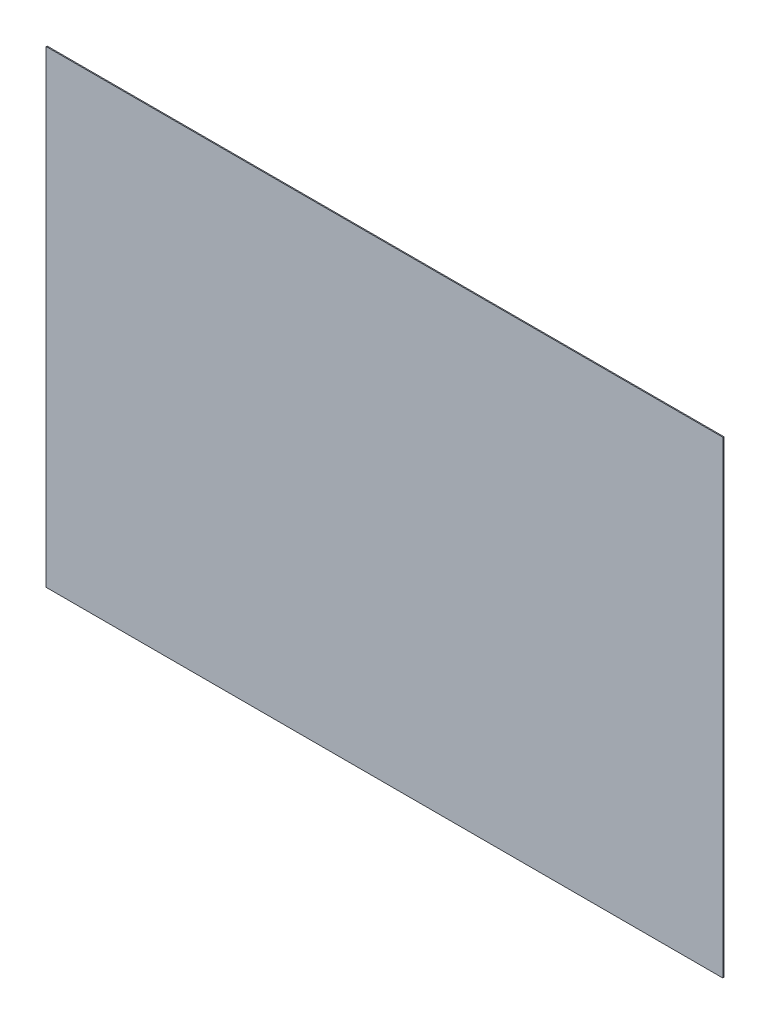
SolidWorks part; units mm, degrees
ref_plane "Alzado" through (0, 0, 0) normal (0, 0, 1) x (1, 0, 0)
ref_plane "Planta" through (0, 0, 0) normal (0, 1, 0) x (1, 0, 0)
ref_plane "Vista lateral" through (0, 0, 0) normal (1, 0, 0) x (0, 0, -1)
sketch "Croquis1" plane through (0, 0, 0) normal (0, 0, 1) x (1, 0, 0)
  line L1 (-650, 450) -> (650, 450)
  line L2 (-650, 450) -> (-650, -450)
  line L3 (-650, -450) -> (650, -450)
  line L4 (650, 450) -> (650, -450)
  line L5 (-650, 450) -> (650, -450) construction
  line L6 (-650, -450) -> (650, 450) construction
  point P0 (0, 0)
  dimension "D1" = 1300
  dimension "D2" = 900
extrude "Saliente-Extruir1" add sketch "Croquis1" along normal blind 1.92
